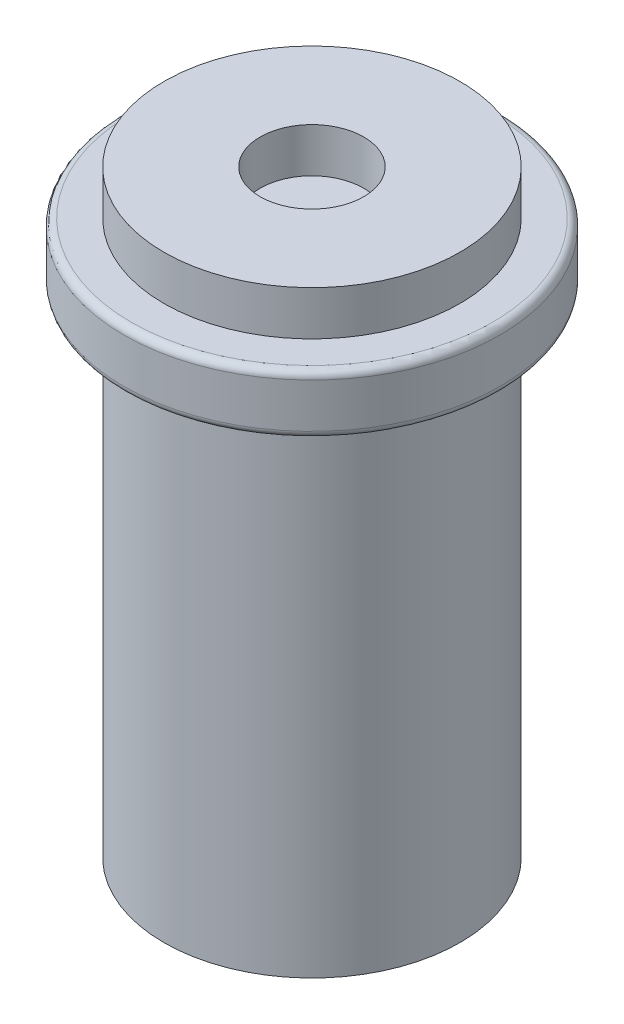
SolidWorks part; units mm, degrees
ref_plane "Спереди" through (0, 0, 0) normal (0, 0, 1) x (1, 0, 0)
ref_plane "Сверху" through (0, 0, 0) normal (0, 1, 0) x (1, 0, 0)
ref_plane "Справа" through (0, 0, 0) normal (1, 0, 0) x (0, 0, -1)
sketch "Эскиз1" plane through (0, 0, 0) normal (0, 1, 0) x (1, 0, 0)
  circle A1 centre (0, 0) radius 10
extrude "Вытянуть1" add sketch "Эскиз1" along normal blind 40.4 from offset 15
sketch "Эскиз2" plane through (0, 55.4, 0) normal (0, 1, 0) x (1, 0, 0)
  circle A0 centre (0, 0) radius 3.5
extrude "Вырез-Вытянуть1" cut sketch "Эскиз2" against normal blind 34
ref_plane "Плоскость1" through (0, 52.4, 0) normal (0, 1, 0) x (-1, 0, 0)
sketch "Эскиз3" plane through (0, 52.4, 0) normal (0, 1, 0) x (-1, 0, 0)
  circle A0 centre (0, 0) radius 12.7
extrude "Вытянуть2" add sketch "Эскиз3" against normal blind 4
fillet "Скругление4" radius 0.5 2 edges at (0, 48.4, 12.7) (0, 52.4, 12.7)
